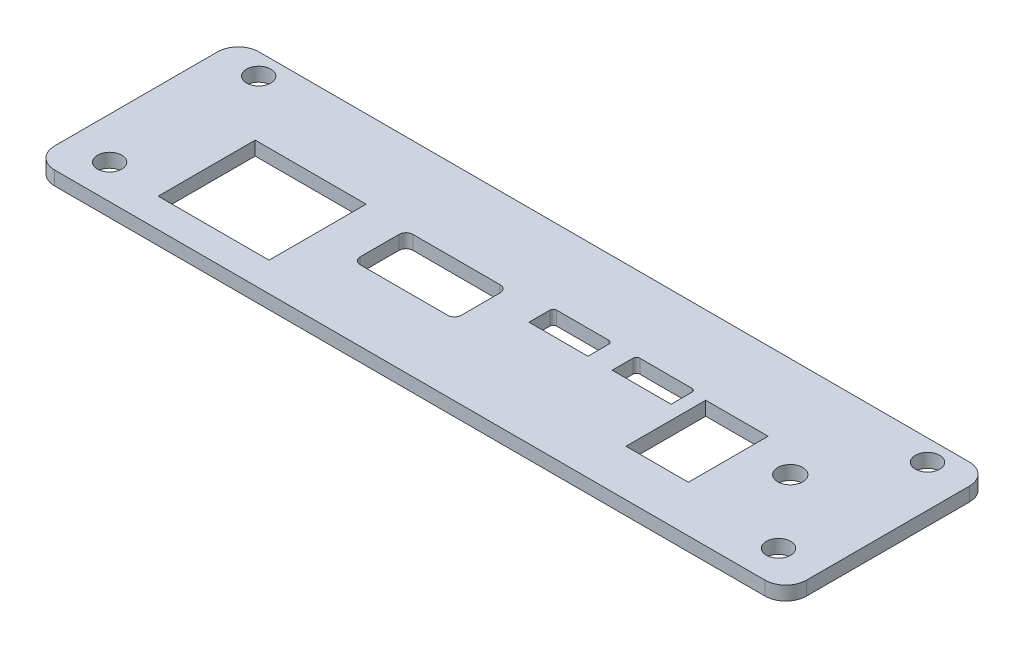
SolidWorks part; units mm, degrees
ref_plane "Front Plane" through (0, 0, 0) normal (0, 0, 1) x (1, 0, 0)
ref_plane "Top Plane" through (0, 0, 0) normal (0, 1, 0) x (1, 0, 0)
ref_plane "Right Plane" through (0, 0, 0) normal (1, 0, 0) x (0, 0, -1)
sketch "Sketch1" plane through (0, 0, 0) normal (0, 1, 0) x (1, 0, 0)
  line L1 (0, 0) -> (108.5, 0)
  line L2 (0, 0) -> (0, 29.5)
  line L3 (0, 29.5) -> (108.5, 29.5)
  line L4 (108.5, 0) -> (108.5, 29.5)
  dimension "D1" = 29.5
  dimension "D2" = 108.5
extrude "Boss-Extrude1" add sketch "Sketch1" along normal blind 2
sketch "Sketch2" plane through (0, 2, 0) normal (0, 1, 0) x (1, 0, 0)
  line L0 (54.25, 29.5) -> (54.25, 0) construction
  line L1 (108.5, 29.5) -> (0, 29.5) construction
  line L2 (0, 0) -> (108.5, 0) construction
  line L3 (0, 14.75) -> (108.5, 14.75) construction
  line L4 (0, 29.5) -> (0, 0) construction
  line L5 (108.5, 0) -> (108.5, 29.5) construction
  circle A0 centre (6, 26.45) radius 1.75
  circle A1 centre (6, 4.95) radius 1.75
  circle A2 centre (102.5, 4.95) radius 1.75
  circle A3 centre (102.5, 26.45) radius 1.75
  dimension "D1" = 3.5
  dimension "D4" = 3.5
  dimension "D2" = 48.25
  dimension "D3" = 11.7
  dimension "D5" = 9.8
  dimension "D6" = 48.25
extrude "Cut-Extrude1" cut sketch "Sketch2" against normal through all
fillet "Fillet1" radius 3 4 edges at (108.5, 1, 0) (108.5, 1, -29.5) (0, 1, 0) (0, 1, -29.5)
sketch "Sketch4" plane through (0, 2, 0) normal (0, 1, 0) x (1, 0, 0)
  line L2 (3, 0) -> (105.5, 0) construction
  line L4 (4, 7.7) -> (104.5, 7.7)
  line L5 (54.25, 29.5) -> (54.25, 0) construction
  line L6 (105.5, 29.5) -> (3, 29.5) construction
  line L7 (4, 7.7) -> (4, 9.7)
  line L8 (4, 9.7) -> (104.5, 9.7)
  line L9 (104.5, 9.7) -> (104.5, 7.7)
  dimension "D3" = 50.25
  dimension "D1" = 50.25
  dimension "D4" = 50.25
  dimension "D5" = 7.7
  dimension "D6" = 2
sketch "Sketch5" plane through (0, 2, 0) normal (0, 1, 0) x (1, 0, 0)
  line L0 (4, 9.7) -> (4, 18.2) construction
  line L1 (4, 18.2) -> (104.5, 18.2) construction
  line L2 (104.5, 18.2) -> (104.5, 9.7) construction
  line L3 (4, 20.2) -> (104.5, 20.2) construction
  line L4 (4, 18.2) -> (4, 20.2) construction
  line L5 (104.5, 18.2) -> (104.5, 20.2) construction
  line L6 (0, 26.5) -> (0, 3) construction
  line L7 (13.75, 18.2) -> (29.75, 18.2)
  line L8 (13.75, 18.2) -> (13.75, 4.2)
  line L9 (13.75, 4.2) -> (29.75, 4.2)
  line L10 (29.75, 18.2) -> (29.75, 4.2)
  line L11 (35.9, 17.8) -> (35.9, 10.2)
  line L12 (50.5, 17.8) -> (50.5, 10.2)
  line L13 (35.9, 10.2) -> (50.5, 10.2)
  line L15 (35.9, 17.8) -> (50.5, 17.8)
  line L16 (56.25, 18.2) -> (56.25, 15.2)
  line L17 (56.25, 15.2) -> (64.75, 15.2)
  line L18 (64.75, 18.2) -> (64.75, 15.2)
  line L20 (68.25, 18.2) -> (68.25, 15.2)
  line L21 (68.25, 15.2) -> (76.75, 15.2)
  line L22 (76.75, 18.2) -> (76.75, 15.2)
  line L23 (78.75, 18.2) -> (87.75, 18.2)
  line L24 (78.75, 18.2) -> (78.75, 6.7)
  line L25 (78.75, 6.7) -> (87.75, 6.7)
  line L26 (87.75, 18.2) -> (87.75, 6.7)
  line L27 (108.5, 3) -> (108.5, 26.5) construction
  line L30 (56.25, 18.2) -> (56.25, 18.7)
  line L31 (56.25, 18.7) -> (64.75, 18.7)
  line L32 (64.75, 18.2) -> (64.75, 18.7)
  line L34 (68.25, 18.2) -> (68.25, 18.7)
  line L35 (68.25, 18.7) -> (76.75, 18.7)
  line L36 (76.75, 18.2) -> (76.75, 18.7)
  circle A0 centre (94.15, 15) radius 1.8
  point P24 (64.75, 16.7)
  point P25 (68.25, 16.7)
  point P30 (76.75, 16.7)
  point P38 (56.25, 16.7)
  dimension "D17" = 3.6
  dimension "D1" = 8.5
  dimension "D3" = 16
  dimension "D4" = 14
  dimension "D5" = 14.6
  dimension "D6" = 6.15
  dimension "D7" = 8
  dimension "D8" = 8.5
  dimension "D9" = 3
  dimension "D10" = 11.5
  dimension "D11" = 8.5
  dimension "D12" = 3
  dimension "D13" = 3.5
  dimension "D14" = 9
  dimension "D16" = 2
  dimension "D18" = 6.4
  dimension "D19" = 3.2
  dimension "D20" = 13.75
  dimension "D21" = 14.35
  dimension "D22" = 108.5
  dimension "D25" = 64.75
  dimension "D26" = 56.25
  dimension "D27" = 0.5
  dimension "D28" = 0.5
  dimension "D29" = 7.6
  dimension "D2" = 2
extrude "Cut-Extrude2" cut sketch "Sketch5" against normal through all
fillet "Fillet2" radius 1 4 edges at (35.9, 1, -17.8) (50.5, 1, -17.8) (50.5, 1, -10.2) (35.9, 1, -10.2)
fillet "Fillet3" radius 0.5 4 edges at (76.75, 1, -18.7) (64.75, 1, -18.7) (68.25, 1, -18.7) (56.25, 1, -18.7)
